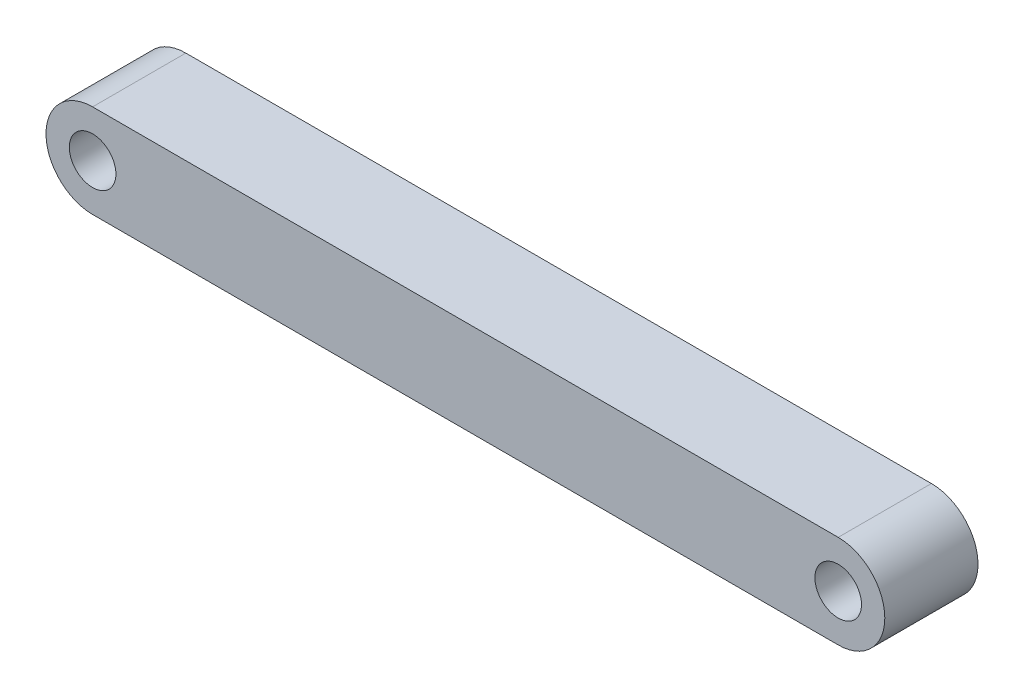
SolidWorks part; units mm, degrees
ref_plane "前视基准面" through (0, 0, 0) normal (0, 0, 1) x (1, 0, 0)
ref_plane "上视基准面" through (0, 0, 0) normal (0, 1, 0) x (1, 0, 0)
ref_plane "右视基准面" through (0, 0, 0) normal (1, 0, 0) x (0, 0, -1)
sketch "草图1" plane through (0, 0, 0) normal (0, 0, 1) x (1, 0, 0)
  line L0 (-40, 0) -> (40, 0) construction
  line L1 (-40, 5) -> (40, 5)
  line L2 (-40, -5) -> (40, -5)
  arc A0 (-40, 5) -> (-40, -5) centre (-40, 0) ccw
  arc A1 (40, -5) -> (40, 5) centre (40, 0) ccw
  point P2 (0, 0)
extrude "凸台-拉伸1" add sketch "草图1" along normal blind 10
sketch "草图2" plane through (0, 0, 10) normal (0, 0, 1) x (1, 0, 0)
  circle A0 centre (-40, 0) radius 2.5
  circle A1 centre (40, 0) radius 2.5
extrude "切除-拉伸1" cut sketch "草图2" against normal through all
